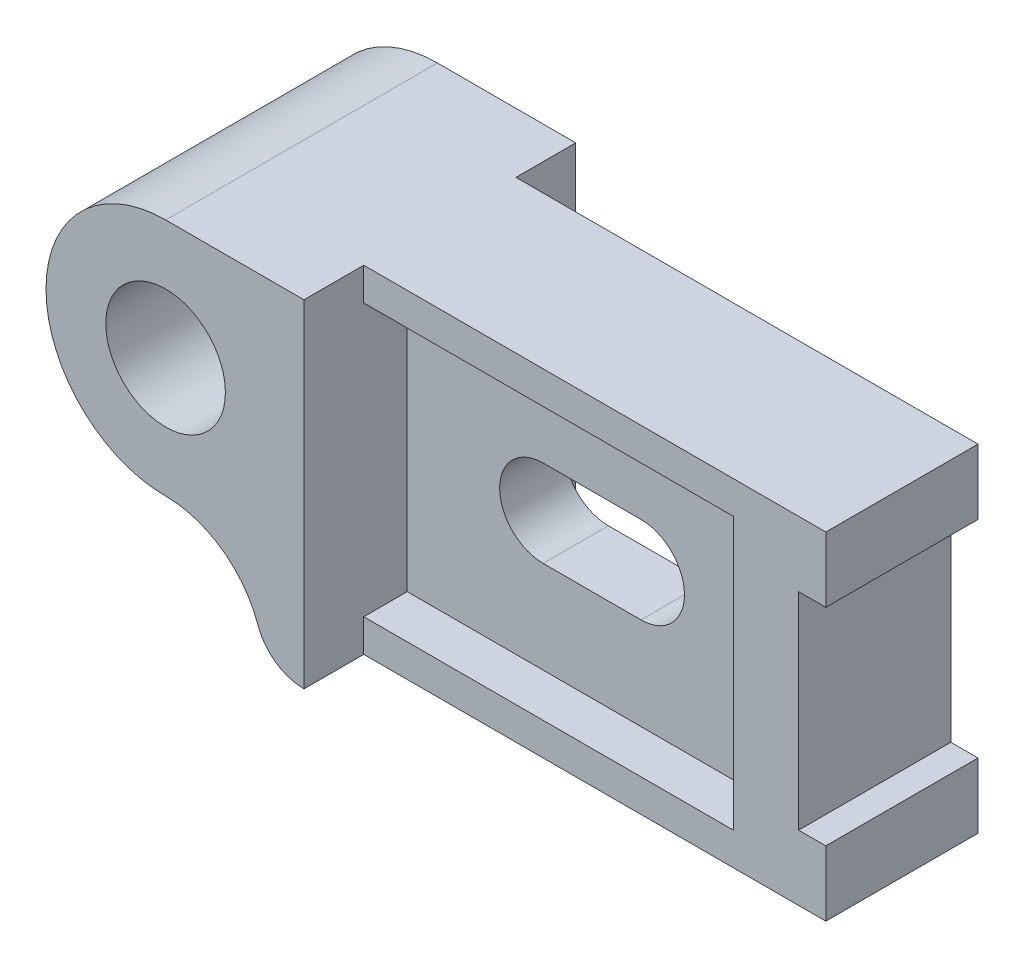
SolidWorks part; units mm, degrees
ref_plane "Front Plane" through (0, 0, 0) normal (0, 0, 1) x (1, 0, 0)
ref_plane "Top Plane" through (0, 0, 0) normal (0, 1, 0) x (1, 0, 0)
ref_plane "Right Plane" through (0, 0, 0) normal (1, 0, 0) x (0, 0, -1)
sketch "Sketch1" plane through (0, 0, 0) normal (0, 0, 1) x (1, 0, 0)
  line L0 (0, 22) -> (25.4537, 22)
  line L1 (25.4537, 22) -> (25.4537, -40)
  arc A0 (0, 22) -> (0, -22) centre (0, 0) ccw
  circle A1 centre (0, 0) radius 11
  arc A2 (0, -22) -> (16.9174, -33.8516) centre (0, -40) cw
  arc A3 (25.4537, -40) -> (16.9174, -33.8516) centre (25.4537, -31) cw
  dimension "D1" = 44
  dimension "D2" = 22
  dimension "D4" = 18
  dimension "D5" = 9
  dimension "D3" = 62
extrude "Boss-Extrude1" add sketch "Sketch1" against normal blind 50
sketch "Sketch2" plane through (25.4537, 0, 0) normal (1, 0, 0) x (0, 0, -1)
  line L0 (50, 22) -> (0, 22) construction
  line L1 (11, 22) -> (39, 22)
  line L2 (11, 22) -> (11, 16)
  line L3 (11, 16) -> (39, 16)
  line L4 (39, 22) -> (39, 16)
  line L5 (50, -40) -> (0, -40) construction
  line L6 (11, -40) -> (39, -40)
  line L7 (11, -40) -> (11, -34)
  line L8 (11, -34) -> (39, -34)
  line L9 (39, -40) -> (39, -34)
  line L10 (50, -40) -> (50, 22) construction
  point P20 (24.0392, 30.3824)
  dimension "D1" = 11
  dimension "D2" = 28
  dimension "D3" = 28
  dimension "D4" = 11
  dimension "D5" = 6
  dimension "D6" = 6
extrude "Boss-Extrude2" add sketch "Sketch2" along normal blind 68
sketch "Sketch3" plane through (25.4537, 0, 0) normal (1, 0, 0) x (0, 0, -1)
  line L0 (11, 16) -> (39, 16) construction
  line L1 (19, 16) -> (31, 16)
  line L2 (19, 16) -> (19, -34)
  line L3 (19, -34) -> (31, -34)
  line L4 (31, 16) -> (31, -34)
  line L5 (39, -34) -> (11, -34) construction
  line L6 (0, -40) -> (0, 22) construction
  line L7 (50, -40) -> (50, 22) construction
  dimension "D1" = 19
  dimension "D2" = 19
extrude "Boss-Extrude3" add sketch "Sketch3" along normal blind 68
sketch "Sketch4" plane through (93.4537, 0, 0) normal (1, 0, 0) x (0, 0, -1)
  line L1 (11, 22) -> (39, 22)
  line L2 (11, 22) -> (11, -40)
  line L3 (11, -40) -> (39, -40)
  line L4 (39, 22) -> (39, -40)
extrude "Boss-Extrude4" add sketch "Sketch4" along normal blind 12
sketch "Sketch5" plane through (105.4537, 0, 0) normal (1, 0, 0) x (0, 0, -1)
  line L0 (39, -40) -> (39, 22) construction
  line L1 (11, 22) -> (39, 22)
  line L2 (11, 22) -> (11, 10)
  line L3 (11, 10) -> (39, 10)
  line L4 (39, 22) -> (39, 10)
  line L10 (11, -40) -> (39, -40)
  line L11 (11, -40) -> (11, -28)
  line L12 (11, -28) -> (39, -28)
  line L13 (39, -40) -> (39, -28)
  dimension "D1" = 12
  dimension "D2" = 12
extrude "Boss-Extrude5" add sketch "Sketch5" along normal blind 5
sketch "Sketch8" plane through (0, 0, -19) normal (0, 0, 1) x (1, 0, 0)
  line L0 (50.4537, -9) -> (68.4537, -9) construction
  line L1 (50.4537, -1) -> (68.4537, -1)
  line L2 (50.4537, -17) -> (68.4537, -17)
  line L3 (25.4537, -40) -> (25.4537, 22) construction
  line L4 (93.4537, -34) -> (25.4537, -34) construction
  arc A0 (50.4537, -1) -> (50.4537, -17) centre (50.4537, -9) ccw
  arc A1 (68.4537, -17) -> (68.4537, -1) centre (68.4537, -9) ccw
  point P2 (59.4537, -9)
  dimension "D1" = 16
  dimension "D2" = 18
  dimension "D3" = 25
  dimension "D4" = 25
extrude "Cut-Extrude1" cut sketch "Sketch8" against normal through all
